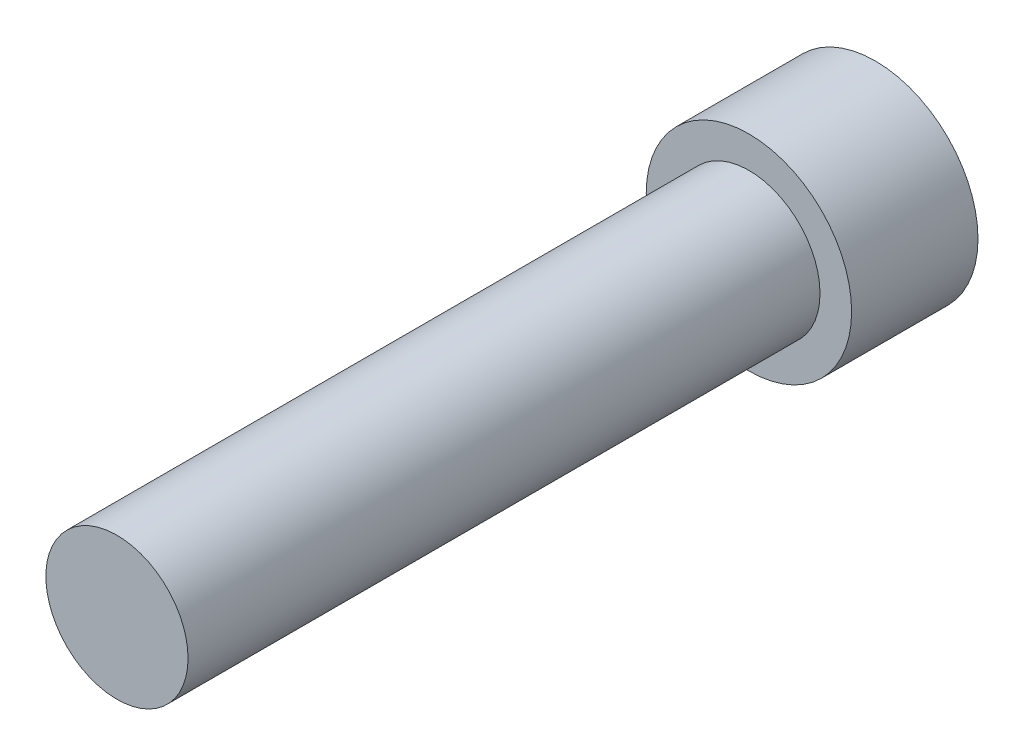
SolidWorks part; units mm, degrees
material "사용자정의 플라스틱"
ref_plane "정면" through (0, 0, 0) normal (0, 0, 1) x (1, 0, 0)
ref_plane "윗면" through (0, 0, 0) normal (0, 1, 0) x (1, 0, 0)
ref_plane "우측면" through (0, 0, 0) normal (1, 0, 0) x (0, 0, -1)
sketch "스케치1" plane through (0, 0, 0) normal (0, 0, 1) x (1, 0, 0)
  circle A0 centre (0, 0) radius 4.5
  dimension "D1" = 9
extrude "보스-돌출1" add sketch "스케치1" along normal blind 40
sketch "스케치2" plane through (0, 0, 0) normal (0, 0, -1) x (-1, 0, 0)
  circle A0 centre (0, 0) radius 6.5
  dimension "D1" = 13
extrude "보스-돌출2" add sketch "스케치2" along normal blind 8
sketch "스케치3" plane through (0, 0, -8) normal (0, 0, -1) x (-1, 0, 0)
  line L1 (1.5166, -2.2986) -> (2.7333, -0.3357)
  line L2 (2.7489, 0.1641) -> (1.6573, 2.1992)
  line L3 (1.2323, 2.4627) -> (-1.0759, 2.5349)
  line L4 (-1.5166, 2.2986) -> (-2.7333, 0.3357)
  line L5 (-2.7489, -0.1641) -> (-1.6573, -2.1992)
  line L6 (-1.2323, -2.4627) -> (1.0759, -2.5349)
  circle A0 centre (0, 0) radius 2.5 construction
  arc A1 (-1.0759, 2.5349) -> (-1.5166, 2.2986) centre (-1.0916, 2.0351) ccw
  arc A2 (1.6573, 2.1992) -> (1.2323, 2.4627) centre (1.2167, 1.9629) ccw
  arc A3 (2.7333, -0.3357) -> (2.7489, 0.1641) centre (2.3083, -0.0722) ccw
  arc A4 (1.5166, -2.2986) -> (1.0759, -2.5349) centre (1.0916, -2.0351) cw
  arc A5 (-1.6573, -2.1992) -> (-1.2323, -2.4627) centre (-1.2167, -1.9629) ccw
  arc A6 (-2.7333, 0.3357) -> (-2.7489, -0.1641) centre (-2.3083, 0.0722) ccw
  dimension "D2" = 0.5
  dimension "D1" = 5
extrude "컷-돌출1" cut sketch "스케치3" against normal blind 4
